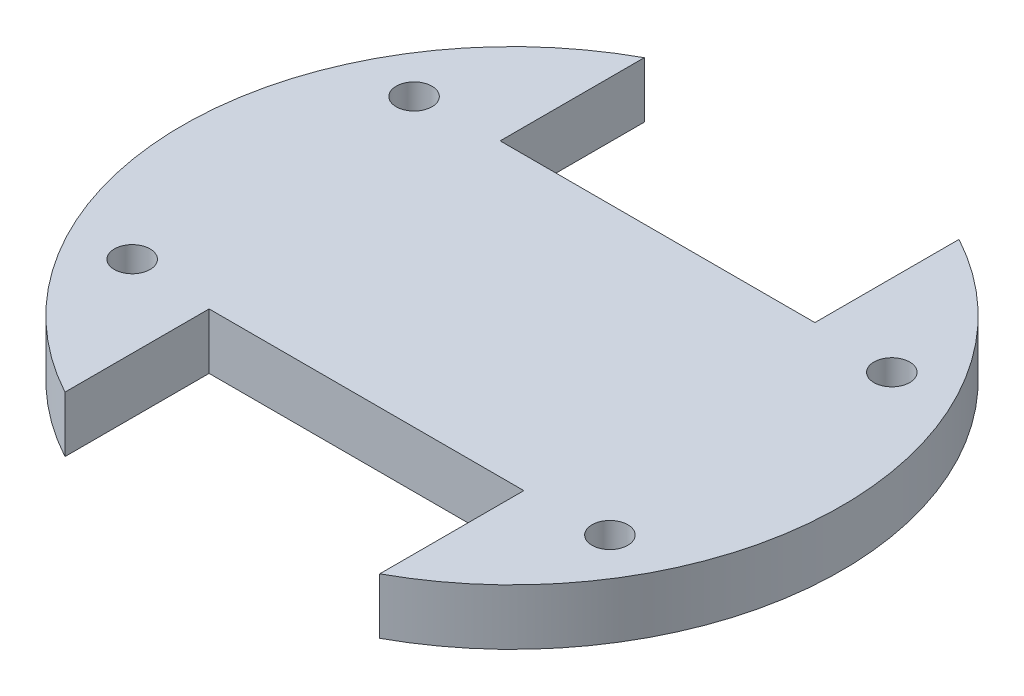
SolidWorks part; units mm, degrees
ref_plane "前视基准面" through (0, 0, 0) normal (0, 0, 1) x (1, 0, 0)
ref_plane "上视基准面" through (0, 0, 0) normal (0, 1, 0) x (1, 0, 0)
ref_plane "右视基准面" through (0, 0, 0) normal (1, 0, 0) x (0, 0, -1)
sketch "草图1" plane through (0, 0, 0) normal (0, 1, 0) x (1, 0, 0)
  circle A0 centre (0, 0) radius 29.5
  dimension "D1" = 59
extrude "凸台-拉伸1" add sketch "草图1" along normal blind 5 contours A0
sketch "草图2" plane through (0, 5, 0) normal (0, 1, 0) x (1, 0, 0)
  line L0 (-42.9641, 0) -> (48.0853, 0) construction
  line L1 (0, 36.4097) -> (0, -43.4956) construction
  line L6 (0, -45.977) -> (0, -13.023) construction
  line L7 (-14.0831, 13.023) -> (14.0831, 13.023)
  line L8 (-14.0831, 13.023) -> (-14.0831, 45.977)
  line L9 (-14.0831, 45.977) -> (14.0831, 45.977)
  line L10 (14.0831, 13.023) -> (14.0831, 45.977)
  line L11 (0, 45.977) -> (0, 13.023) construction
  line L12 (-14.0831, 29.5) -> (14.0831, 29.5) construction
  line L13 (14.0831, -29.5) -> (-14.0831, -29.5) construction
  line L14 (14.0831, -13.023) -> (14.0831, -45.977)
  line L15 (14.0831, -13.023) -> (-14.0831, -13.023)
  line L16 (-14.0831, -13.023) -> (-14.0831, -45.977)
  line L17 (14.0831, -45.977) -> (-14.0831, -45.977)
  circle A0 centre (0, 0) radius 29.5 construction
  point P4 (0, 29.5)
  point P17 (0, -29.5)
  point P26 (0, 0)
  dimension "D1" = 2
extrude "切除-拉伸1" cut sketch "草图2" against normal through all
sketch "草图6" plane through (0, 5, 0) normal (0, 1, 0) x (1, 0, 0)
  line L0 (34.9742, 0) -> (-41.2754, 0) construction
  line L1 (0, 25.4735) -> (0, -31.1397) construction
  circle A10 centre (-21.376, 12.613) radius 1.6
  circle A11 centre (-21.376, -12.613) radius 1.6
  circle A12 centre (21.376, 12.613) radius 1.6
  circle A13 centre (21.376, -12.613) radius 1.6
  point P23 (4.6479, 0)
  dimension "D1" = 25.226
  dimension "D4" = 3.2
  dimension "D3" = 42.752
extrude "切除-拉伸5" cut sketch "草图6" against normal through all
